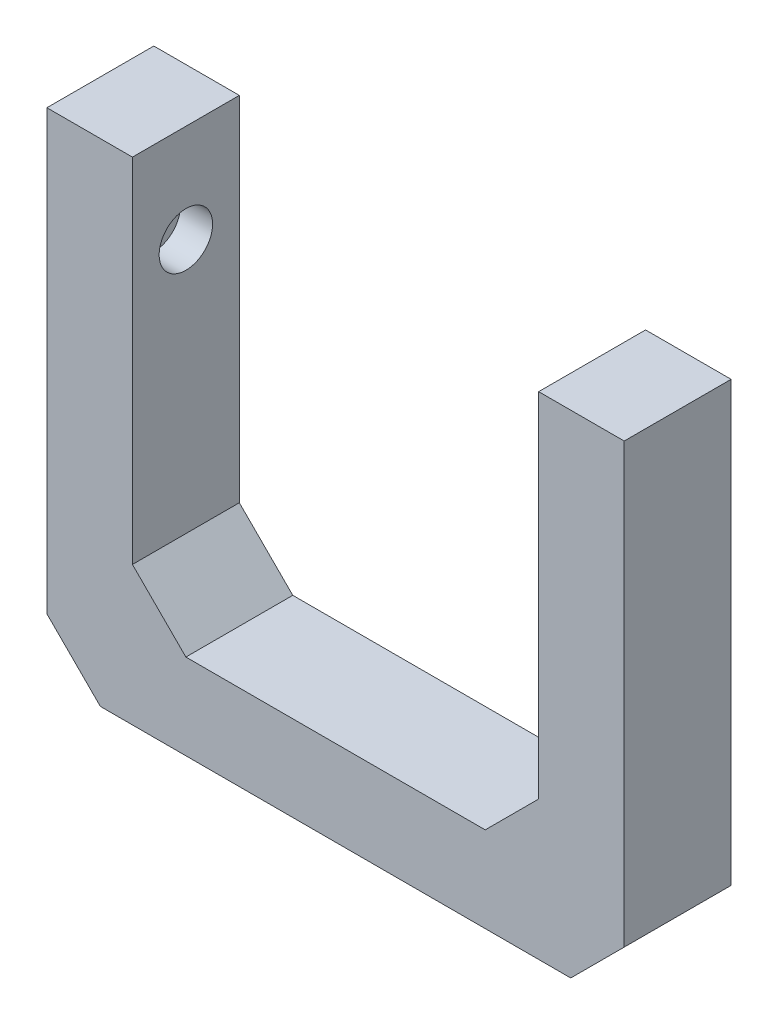
SolidWorks part; units mm, degrees
ref_plane "Front Plane" through (0, 0, 0) normal (0, 0, 1) x (1, 0, 0)
ref_plane "Top Plane" through (0, 0, 0) normal (0, 1, 0) x (1, 0, 0)
ref_plane "Right Plane" through (0, 0, 0) normal (1, 0, 0) x (0, 0, -1)
sketch "Sketch1" plane through (0, 0, 0) normal (0, 0, 1) x (1, 0, 0)
  line L0 (-27, 38) -> (-19, 38)
  line L1 (-19, 38) -> (-19, 5)
  line L2 (-14, 0) -> (14, 0)
  line L3 (19, 5) -> (19, 38)
  line L4 (19, 38) -> (27, 38)
  line L5 (27, 38) -> (27, -3)
  line L6 (22, -8) -> (-22, -8)
  line L7 (-27, -3) -> (-27, 38)
  line L8 (-19, 5) -> (-14, 0)
  line L9 (-22, -8) -> (-27, -3)
  line L10 (14, 0) -> (19, 5)
  line L11 (27, -3) -> (22, -8)
  point P3 (-19, 0)
  point P4 (19, 0)
  point P7 (27, -8)
  point P8 (-27, -8)
  dimension "D1" = 8
  dimension "D2" = 8
  dimension "D3" = 38
  dimension "D4" = 46
extrude "Boss-Extrude1" add sketch "Sketch1" along normal blind 10
sketch "Sketch2" plane through (-19, 0, 0) normal (1, 0, 0) x (0, 0, -1)
  line L0 (-10, 38) -> (0, 38) construction
  circle A0 centre (-5, 28.83) radius 2.5
  point P4 (-5, 38)
  dimension "D1" = 5
  dimension "D2" = 9.17
extrude "Cut-Extrude1" cut sketch "Sketch2" against normal blind 3
sketch "Sketch3" plane through (19, 0, 0) normal (-1, 0, 0) x (0, 0, 1)
  line L2 (5.3583, 38.8962) -> (5.3583, 26.8962) construction
  line L3 (8.8583, 38.8962) -> (8.8583, 26.8962)
  line L4 (1.8583, 38.8962) -> (1.8583, 26.8962)
  arc A2 (8.8583, 38.8962) -> (1.8583, 38.8962) centre (5.3583, 38.8962) ccw
  arc A3 (1.8583, 26.8962) -> (8.8583, 26.8962) centre (5.3583, 26.8962) ccw
  point P2 (5.3583, 32.8962)
  point P7 (5.3583, 29.6309)
  point P8 (5.3583, 42.3962)
  point P9 (5.3583, 23.3962)
  dimension "D1" = 7
  dimension "D2" = 19
